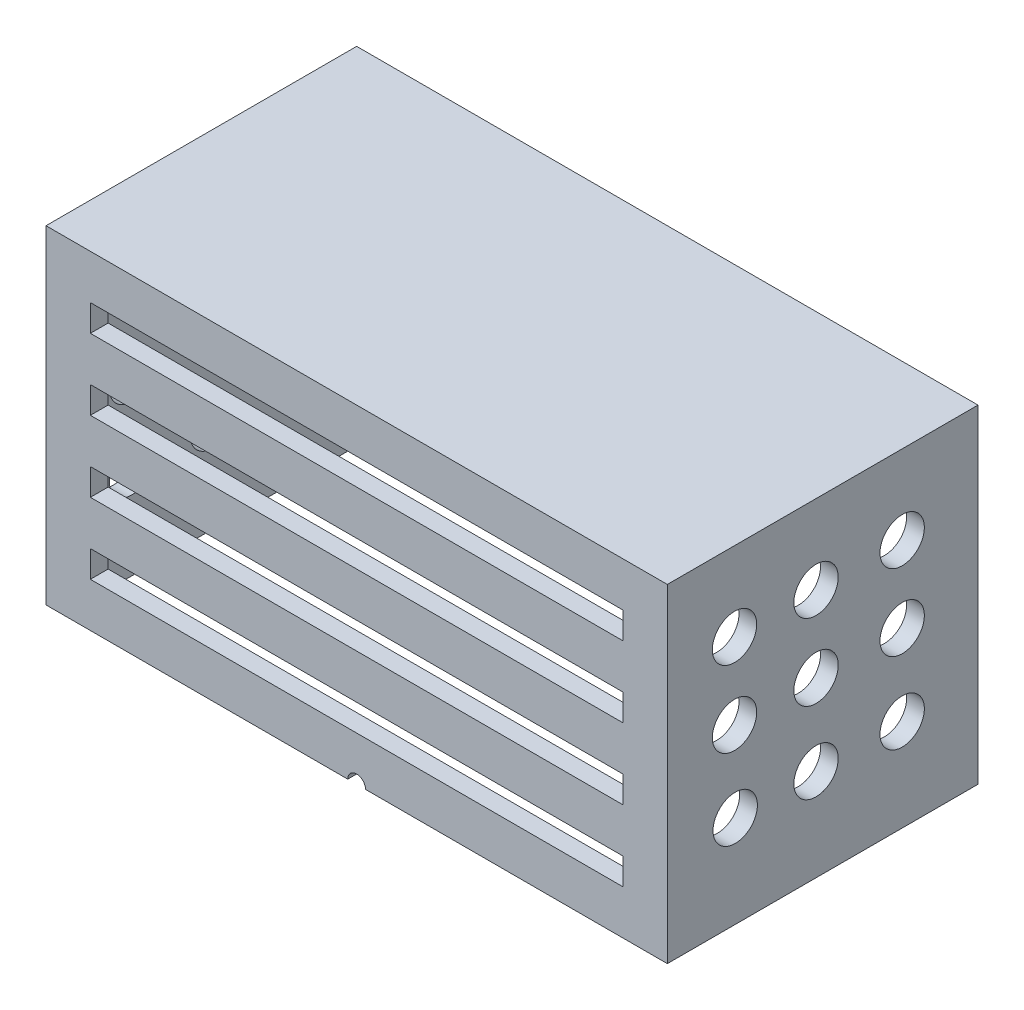
SolidWorks part; units mm, degrees
ref_plane "Front Plane" through (0, 0, 0) normal (0, 0, 1) x (1, 0, 0)
ref_plane "Top Plane" through (0, 0, 0) normal (0, 1, 0) x (1, 0, 0)
ref_plane "Right Plane" through (0, 0, 0) normal (1, 0, 0) x (0, 0, -1)
sketch "Sketch1" plane through (0, 0, 0) normal (0, 1, 0) x (1, 0, 0)
  line L1 (-79.9683, 34.6921) -> (-9.9683, 34.6921)
  line L2 (-79.9683, 34.6921) -> (-79.9683, -0.3079)
  line L3 (-79.9683, -0.3079) -> (-9.9683, -0.3079)
  line L4 (-9.9683, 34.6921) -> (-9.9683, -0.3079)
  dimension "D1" = 70
  dimension "D2" = 35
extrude "Boss-Extrude1" add sketch "Sketch1" along normal blind 37
shell "Shell1" thickness 2
sketch "Sketch2" plane through (0, 0, 0.3079) normal (0, 0, 1) x (1, 0, 0)
  line L1 (-79.9683, 0) -> (-9.9683, 0) construction
  line L3 (-44.9683, 0) -> (-45.9683, 0)
  line L4 (-45.9683, 0) -> (-44.9683, 0)
  line L5 (-44.9683, 0) -> (-43.9683, 0)
  line L6 (-43.9683, 0) -> (-44.9683, 0)
  arc A0 (-45.9683, 0) -> (-43.9683, 0) centre (-44.9683, 0) cw
  line M1 (-79.9683, 0) -> (-9.9683, 0)
  dimension "D1" = 35
  dimension "D3" = 1
  dimension "D4" = 1
extrude "Cut-Extrude1" cut sketch "Sketch2" against normal blind 2 contours A0 M1
sketch "Sketch3" plane through (0, 0, -34.6921) normal (0, 0, -1) x (-1, 0, 0)
  line L0 (14.9683, 0) -> (14.9683, 30)
  line L1 (9.9683, 0) -> (79.9683, 0) construction
  line L2 (14.9683, 30) -> (74.9683, 30)
  line L3 (74.9683, 30) -> (74.9683, 0)
  line L4 (14.9683, 0) -> (74.9683, 0)
  line M4 (9.9683, 0) -> (79.9683, 0)
  dimension "D1" = 5
  dimension "D2" = 5
  dimension "D3" = 30
extrude "Cut-Extrude3" cut sketch "Sketch3" against normal blind 2 contours L3 L2 L0 M4
sketch "Sketch4" plane through (0, 0, 0.3079) normal (0, 0, 1) x (1, 0, 0)
  line L0 (-79.9683, 37) -> (-79.9683, 0) construction
  line L1 (-74.9683, 32) -> (-14.9683, 32)
  line L2 (-74.9683, 32) -> (-74.9683, 29)
  line L3 (-74.9683, 29) -> (-14.9683, 29)
  line L4 (-14.9683, 32) -> (-14.9683, 29)
  line L5 (-14.9683, 24) -> (-74.9683, 24)
  line L6 (-14.9683, 24) -> (-14.9683, 21)
  line L7 (-14.9683, 21) -> (-74.9683, 21)
  line L8 (-74.9683, 24) -> (-74.9683, 21)
  line L9 (-9.9683, 37) -> (-9.9683, 0) construction
  line L10 (-79.9683, 37) -> (-9.9683, 37) construction
  line L12 (-74.9683, 8) -> (-14.9683, 8)
  line L13 (-14.9683, 16) -> (-74.9683, 16)
  line L14 (-14.9683, 16) -> (-14.9683, 13)
  line L15 (-14.9683, 13) -> (-74.9683, 13)
  line L16 (-74.9683, 16) -> (-74.9683, 13)
  line L17 (-74.9683, 8) -> (-74.9683, 5)
  line L18 (-74.9683, 5) -> (-14.9683, 5)
  line L19 (-14.9683, 8) -> (-14.9683, 5)
  dimension "D1" = 5
  dimension "D2" = 5
  dimension "D3" = 3
  dimension "D4" = 3
  dimension "D5" = 3
  dimension "D6" = 60
  dimension "D7" = 5
  dimension "D8" = 5
  dimension "D9" = 5
  dimension "D10" = 5
  dimension "D11" = 5
  dimension "D12" = 5
  dimension "D13" = 5
  dimension "D14" = 3
  dimension "D15" = 5
  dimension "D16" = 5
  dimension "D17" = 5
extrude "Cut-Extrude4" cut sketch "Sketch4" against normal blind 2 contours L13 L16 L15 L14 | L5 L8 L7 L6 | L4 L1 L2 L3 | L12 L19 L18 L17
sketch "Sketch5" plane through (-79.9683, 0, 0) normal (-1, 0, 0) x (0, 0, 1)
  circle A0 centre (-26.1494, 28.0917) radius 2.5
  circle A1 centre (-26.1494, 19.5077) radius 2.5
  circle A2 centre (-26.1494, 10.4011) radius 2.5
  circle A3 centre (-16.4457, 10.4011) radius 2.5
  circle A4 centre (-7.3391, 10.4011) radius 2.5
  circle A5 centre (-7.3391, 19.5077) radius 2.5
  circle A6 centre (-16.4457, 19.5077) radius 2.5
  circle A7 centre (-7.3391, 28.0917) radius 2.5
  circle A8 centre (-16.4457, 28.0917) radius 2.5
  dimension "D1" = 5
  dimension "D2" = 5
  dimension "D3" = 5
  dimension "D4" = 5
  dimension "D5" = 5
  dimension "D6" = 5
  dimension "D7" = 5
  dimension "D8" = 5
  dimension "D9" = 5
extrude "Cut-Extrude5" cut sketch "Sketch5" against normal blind 2 contours A0 | A1 | A2 | A3 | A6 | A8 | A7 | A5 | A4
sketch "Sketch6" plane through (-9.9683, 0, 0) normal (1, 0, 0) x (0, 0, -1)
  circle A0 centre (7.2645, 28.0917) radius 2.5
  circle A1 centre (7.2645, 19.5077) radius 2.5
  circle A2 centre (7.3391, 10.4011) radius 2.5
  circle A3 centre (16.4457, 10.4011) radius 2.5
  circle A4 centre (16.4457, 19.5077) radius 2.5
  circle A5 centre (26.1494, 19.5077) radius 2.5
  circle A6 centre (16.4457, 28.0917) radius 2.5
  circle A7 centre (26.1494, 28.0917) radius 2.5
  circle A8 centre (26.1494, 10.4011) radius 2.5
  dimension "D1" = 5
  dimension "D2" = 5
  dimension "D3" = 5
  dimension "D4" = 5
  dimension "D5" = 5
  dimension "D6" = 5
  dimension "D7" = 5
  dimension "D8" = 5
  dimension "D9" = 5
extrude "Cut-Extrude6" cut sketch "Sketch6" against normal blind 2
